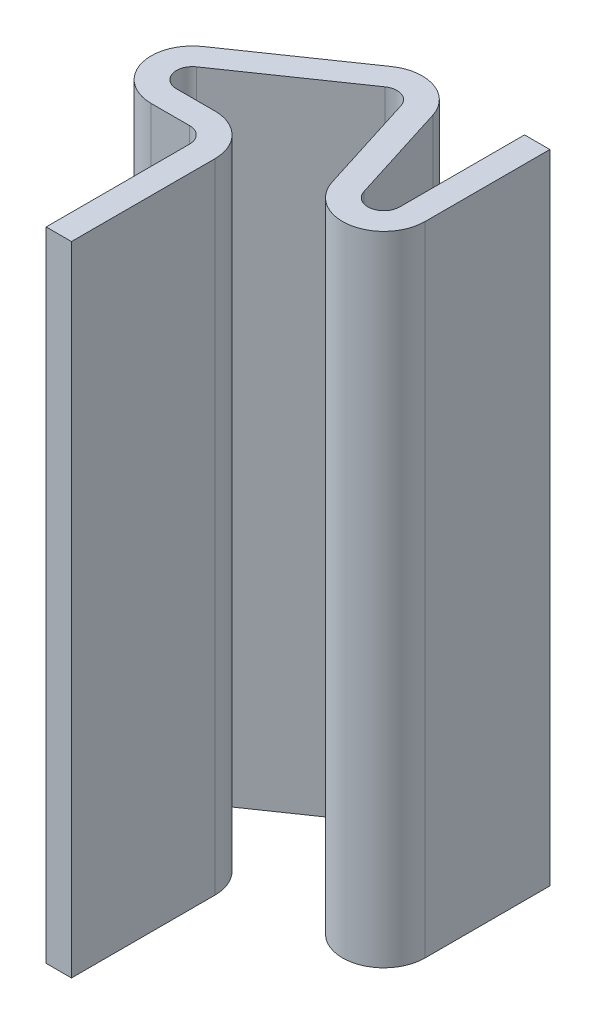
SolidWorks part; units mm, degrees
material "1060 Alloy"
ref_plane "Front Plane" through (0, 0, 0) normal (0, 0, 1) x (1, 0, 0)
ref_plane "Top Plane" through (0, 0, 0) normal (0, 1, 0) x (1, 0, 0)
ref_plane "Right Plane" through (0, 0, 0) normal (1, 0, 0) x (0, 0, -1)
sketch "Sketch1" plane through (0, 0, 0) normal (0, 1, 0) x (1, 0, 0)
  line L0 (1.2937, 0) -> (1.2937, -4.5)
  line L1 (0, 1.2937) -> (-1.2062, 1.2937)
  line L2 (-1.49, 2.2054) -> (2.01, 4.6179)
  line L3 (2.7706, 4.3567) -> (3.767, 1.1982)
  line L4 (6.2946, 1.5875) -> (6.2946, 5.5)
  line L5 (5.5009, 1.5875) -> (5.5009, 5.5)
  line L6 (3.5276, 4.5955) -> (4.524, 1.4371)
  line L7 (-1.9405, 2.859) -> (1.5595, 5.2715)
  line L8 (0, 0.5) -> (-1.2062, 0.5)
  line L9 (0.5, 0) -> (0.5, -4.5)
  line L10 (5.5009, 5.5) -> (6.2946, 5.5)
  line L11 (0.5, -4.5) -> (1.2937, -4.5)
  line L12 (1.5595, 5.2715) -> (3.0009, 6.265) construction
  line L13 (3.0009, 6.265) -> (3.5276, 4.5955) construction
  line L18 (0, 1.2937) -> (1.2937, 1.2937) construction
  line L19 (1.2937, 1.2937) -> (1.2937, 0) construction
  arc A0 (1.2937, 0) -> (0, 1.2937) centre (0, 0) ccw
  arc A1 (-1.2062, 1.2937) -> (-1.49, 2.2054) centre (-1.2063, 1.7937) cw
  arc A2 (2.01, 4.6179) -> (2.7706, 4.3567) centre (2.2937, 4.2063) cw
  arc A3 (3.767, 1.1982) -> (6.2946, 1.5875) centre (5.0009, 1.5875) ccw
  arc A4 (4.524, 1.4371) -> (5.5009, 1.5875) centre (5.0009, 1.5875) ccw
  arc A5 (1.5595, 5.2715) -> (3.5276, 4.5955) centre (2.2937, 4.2063) cw
  arc A6 (-1.2062, 0.5) -> (-1.9405, 2.859) centre (-1.2063, 1.7937) cw
  arc A7 (0.5, 0) -> (0, 0.5) centre (0, 0) ccw
  arc A8 (2.01, 4.6179) -> (2.7706, 4.3567) centre (2.2937, 4.2063) cw construction
  arc A9 (-1.2062, 1.2937) -> (-1.49, 2.2054) centre (-1.2063, 1.7937) cw construction
  arc A10 (3.767, 1.1982) -> (6.2946, 1.5875) centre (5.0009, 1.5875) ccw construction
  point P29 (2.2937, 5.5)
  point P39 (-2.5, 1.7937)
  point P42 (5.0009, 0.2937)
  dimension "D2" = 0.5
  dimension "D3" = 5
  dimension "D4" = 3
  dimension "D5" = 5
  dimension "D6" = 2.5
  dimension "D7" = 1
  dimension "D8" = 1
  dimension "D1" = 0.7937
extrude "Boss-Extrude1" add sketch "Sketch1" along normal mid plane 20
